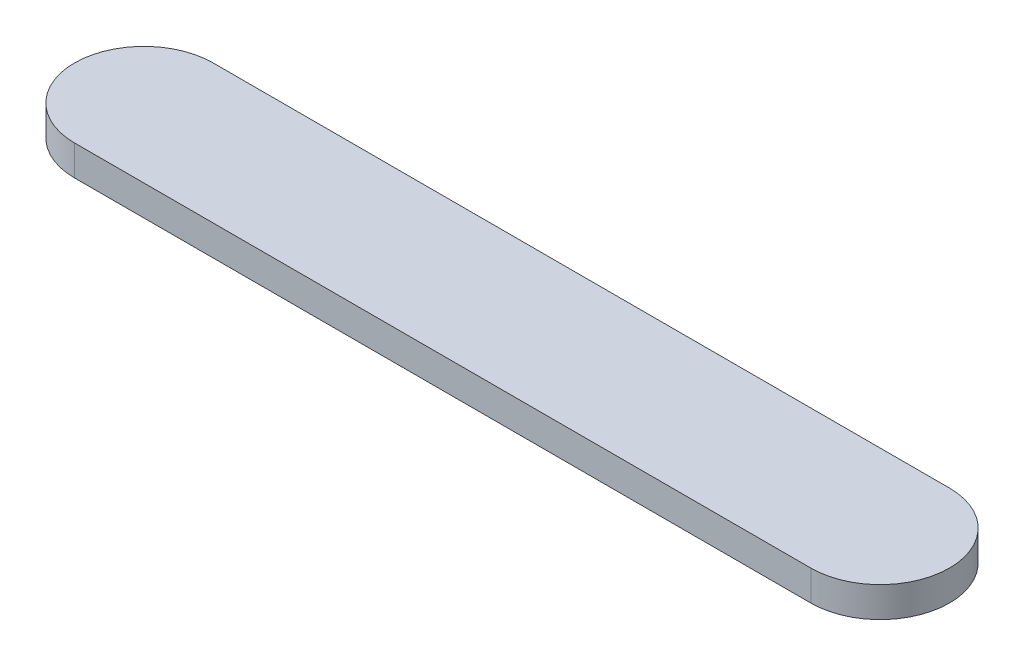
SolidWorks part; units mm, degrees
ref_plane "Front Plane" through (0, 0, 0) normal (0, 0, 1) x (1, 0, 0)
ref_plane "Top Plane" through (0, 0, 0) normal (0, 1, 0) x (1, 0, 0)
ref_plane "Right Plane" through (0, 0, 0) normal (1, 0, 0) x (0, 0, -1)
sketch "Sketch1" plane through (0, 0, 0) normal (0, 1, 0) x (1, 0, 0)
  line L0 (0, 0) -> (85, 0) construction
  line L1 (0, 8) -> (85, 8)
  line L2 (0, -8) -> (85, -8)
  arc A0 (0, 8) -> (0, -8) centre (0, 0) ccw
  arc A1 (85, -8) -> (85, 8) centre (85, 0) ccw
  point P3 (42.5, 0)
  dimension "D1" = 8
  dimension "D2" = 85
extrude "Boss-Extrude1" add sketch "Sketch1" along normal blind 3.5
